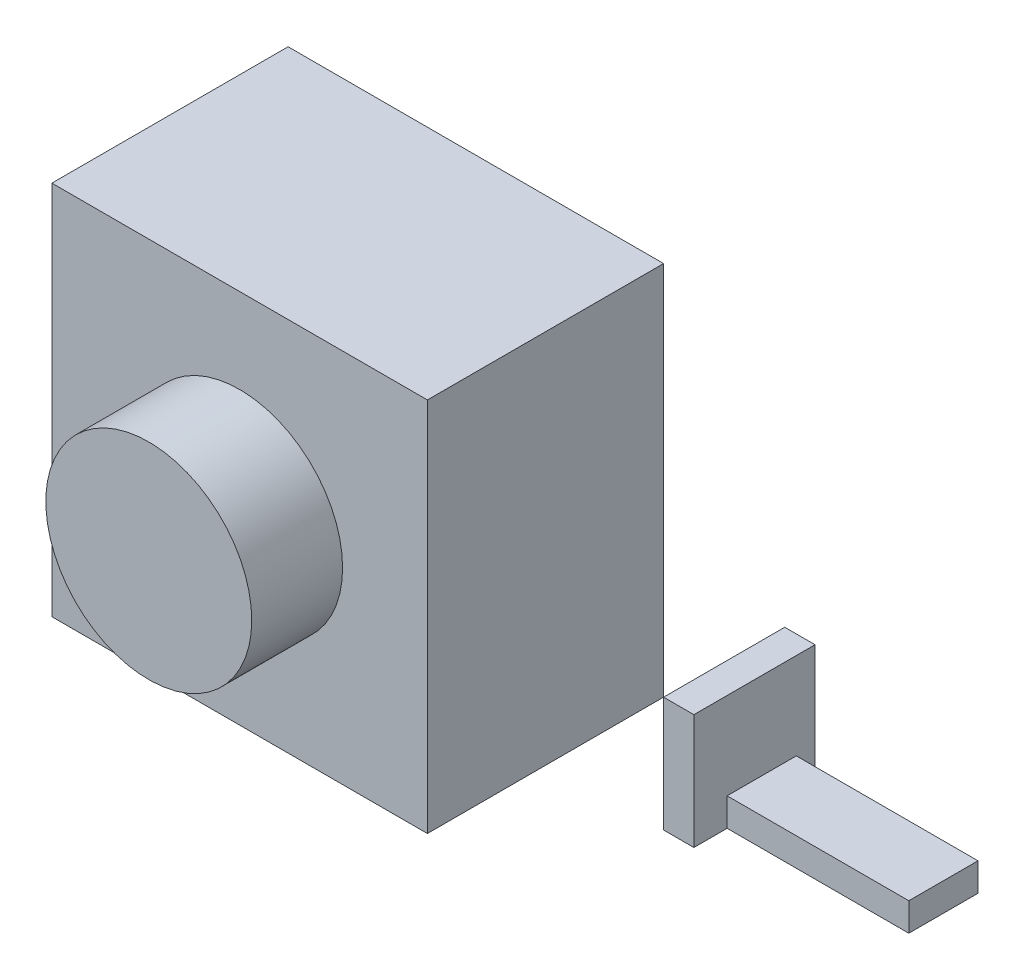
SolidWorks part; units mm, degrees
ref_plane "Front Plane" through (0, 0, 0) normal (0, 0, 1) x (1, 0, 0)
ref_plane "Top Plane" through (0, 0, 0) normal (0, 1, 0) x (1, 0, 0)
ref_plane "Right Plane" through (0, 0, 0) normal (1, 0, 0) x (0, 0, -1)
sketch "Sketch1" plane through (0, 0, 0) normal (0, 1, 0) x (1, 0, 0)
  line L1 (-3.1, -1.95) -> (3.1, -1.95)
  line L2 (-3.1, -1.95) -> (-3.1, 1.95)
  line L3 (-3.1, 1.95) -> (3.1, 1.95)
  line L4 (3.1, -1.95) -> (3.1, 1.95)
  line L5 (-3.1, -1.95) -> (3.1, 1.95) construction
  line L6 (-3.1, 1.95) -> (3.1, -1.95) construction
  point P0 (0, 0)
  dimension "D1" = 3.9
  dimension "D2" = 6.2
extrude "Boss-Extrude1" add sketch "Sketch1" along normal blind 6.2
sketch "Sketch2" plane through (0, 0, 1.95) normal (0, 0, 1) x (1, 0, 0)
  line L0 (3.1, 6.2) -> (3.1, 0) construction
  circle A0 centre (0, 3.1) radius 1.7
  point P7 (3.1, 3.1)
  dimension "D1" = 3.4
extrude "Boss-Extrude2" add sketch "Sketch2" along normal blind 1.5
sketch "Sketch3" plane through (0, 0, 0) normal (0, -1, 0) x (1, 0, 0)
  line L0 (3.1, 1.95) -> (3.1, -1.95) construction
  line L1 (3.1, -1.95) -> (3.6, -1.95)
  line L2 (3.1, -1.95) -> (3.1, -3.95)
  line L3 (3.1, -3.95) -> (3.6, -3.95)
  line L4 (3.6, -1.95) -> (3.6, -3.95)
  line L5 (-3.1, -1.95) -> (-3.1, 1.95) construction
  line L6 (-3.1, -1.95) -> (-3.6, -1.95)
  line L7 (-3.1, -1.95) -> (-3.1, -3.95)
  line L8 (-3.1, -3.95) -> (-3.6, -3.95)
  line L9 (-3.6, -1.95) -> (-3.6, -3.95)
  point P12 (0, 0)
  point P14 (-3.1, -1.95)
  dimension "D1" = 2
  dimension "D2" = 0.5
extrude "Boss-Extrude3" add sketch "Sketch3" along normal blind 1.9 separate body
sketch "Sketch4" plane through (3.6, 0, 0) normal (1, 0, 0) x (0, 0, -1)
  line L0 (3.95, -1.9) -> (1.95, -1.9) construction
  line L1 (2.4985, -1.435) -> (3.6408, -1.435)
  line L2 (2.4985, -1.435) -> (2.4985, -1.9)
  line L3 (2.4985, -1.9) -> (3.6408, -1.9)
  line L4 (3.6408, -1.435) -> (3.6408, -1.9)
extrude "Boss-Extrude4" add sketch "Sketch4" along normal blind 3
